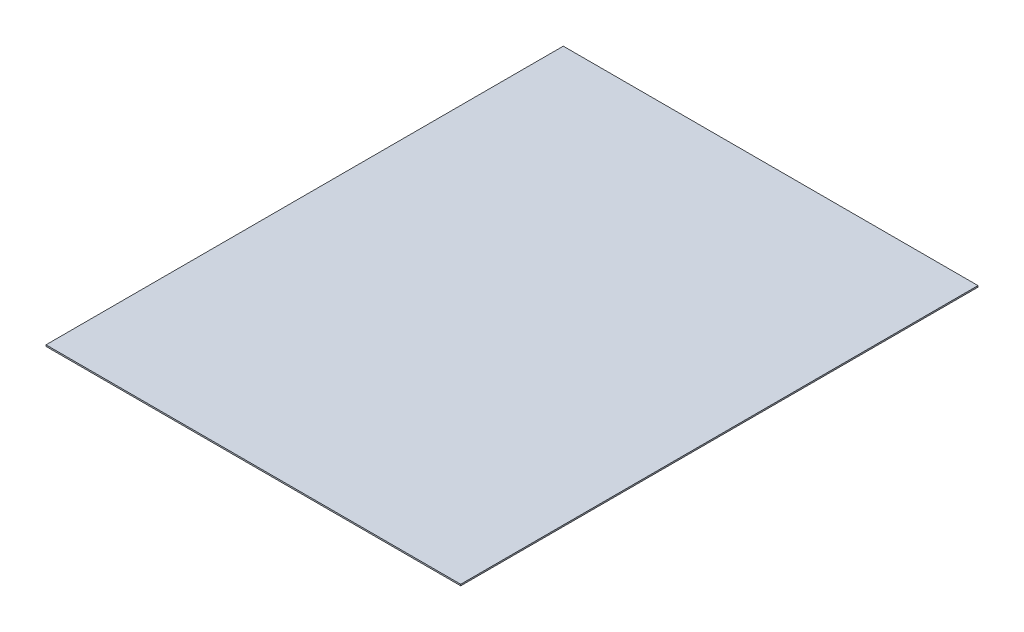
SolidWorks part; units mm, degrees
ref_plane "Front Plane" through (0, 0, 0) normal (0, 0, 1) x (1, 0, 0)
ref_plane "Top Plane" through (0, 0, 0) normal (0, 1, 0) x (1, 0, 0)
ref_plane "Right Plane" through (0, 0, 0) normal (1, 0, 0) x (0, 0, -1)
sketch "Sketch1" plane through (0, 0, 0) normal (0, 1, 0) x (1, 0, 0)
  line L1 (0, 0) -> (7404.2173, 0)
  line L2 (0, 0) -> (0, 9235.4845)
  line L3 (0, 9235.4845) -> (7404.2173, 9235.4845)
  line L4 (7404.2173, 0) -> (7404.2173, 9235.4845)
extrude "Boss-Extrude1" add sketch "Sketch1" along normal blind 25.4
